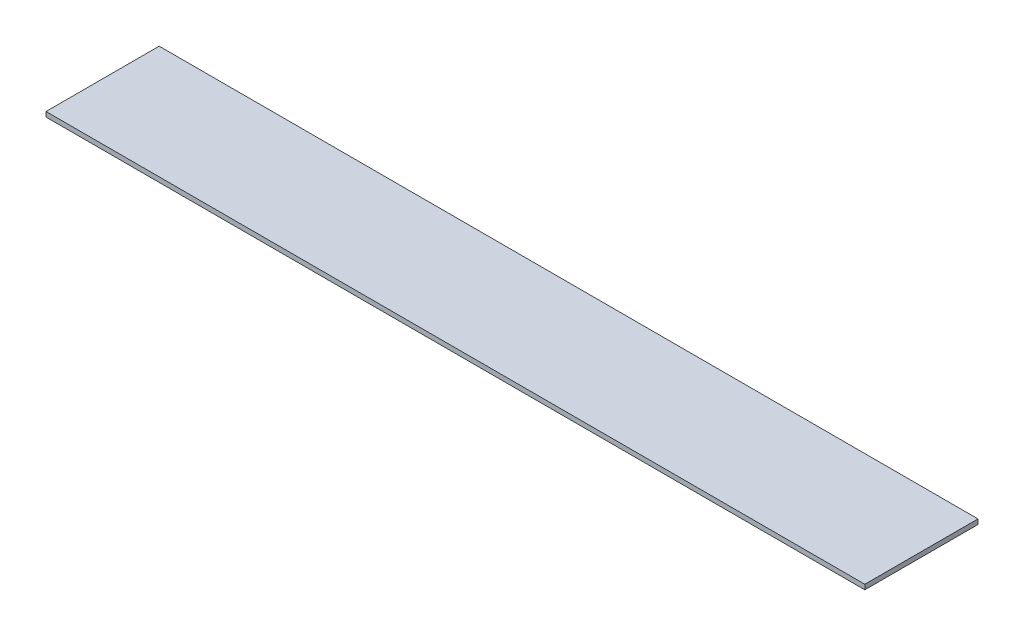
SolidWorks part; units mm, degrees
ref_plane "Alzado" through (0, 0, 0) normal (0, 0, 1) x (1, 0, 0)
ref_plane "Planta" through (0, 0, 0) normal (0, 1, 0) x (1, 0, 0)
ref_plane "Vista lateral" through (0, 0, 0) normal (1, 0, 0) x (0, 0, -1)
sketch "Croquis1" plane through (0, 0, 0) normal (0, 1, 0) x (1, 0, 0)
  line L1 (253.25, -35) -> (-253.25, -35)
  line L2 (253.25, -35) -> (253.25, 35)
  line L3 (253.25, 35) -> (-253.25, 35)
  line L4 (-253.25, -35) -> (-253.25, 35)
  line L5 (253.25, -35) -> (-253.25, 35) construction
  line L6 (253.25, 35) -> (-253.25, -35) construction
  point P0 (0, 0)
  dimension "D1" = 506.5
  dimension "D2" = 70
extrude "Extruir1" add sketch "Croquis1" along normal blind 3
